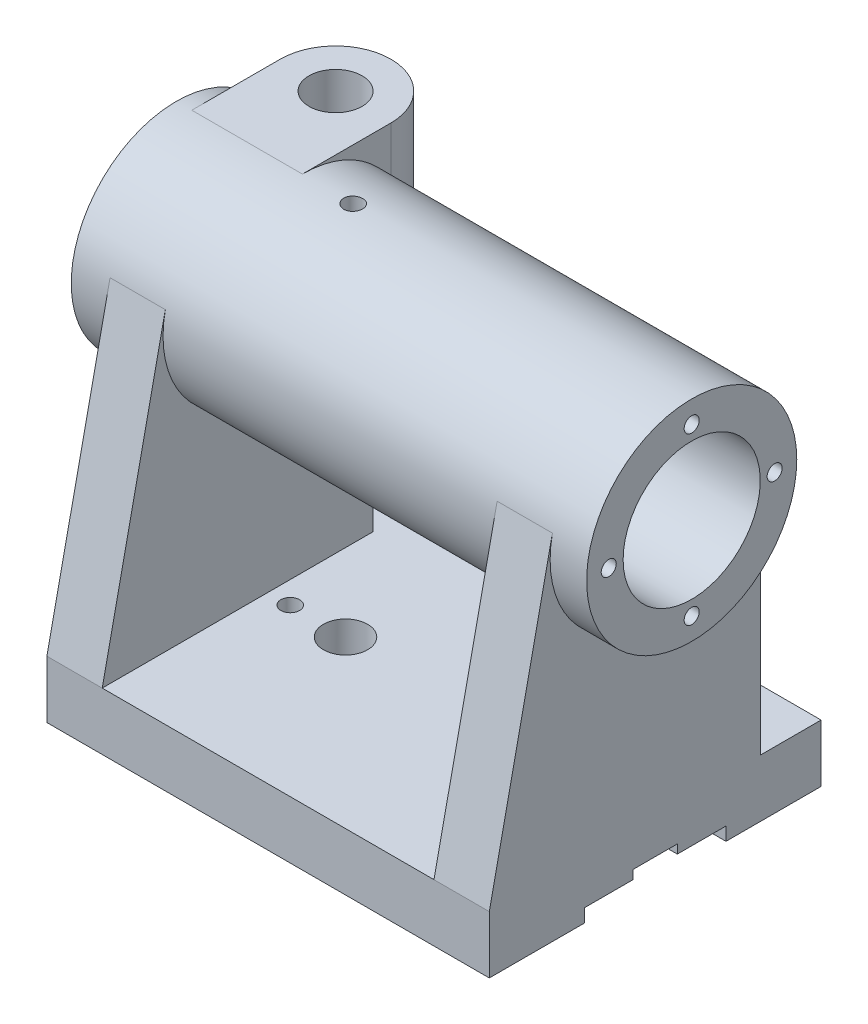
SolidWorks part; units mm, degrees
ref_plane "前视基准面" through (0, 0, 0) normal (0, 0, 1) x (1, 0, 0)
ref_plane "上视基准面" through (0, 0, 0) normal (0, 1, 0) x (1, 0, 0)
ref_plane "右视基准面" through (0, 0, 0) normal (1, 0, 0) x (0, 0, -1)
sketch "草图2" plane through (0, 0, 0) normal (1, 0, 0) x (0, 0, -1)
  circle A0 centre (0, 0) radius 47.5
  dimension "D1" = 95
extrude "凸台-拉伸1" add sketch "草图2" along normal blind 233
sketch "草图4" plane through (0, 0, 0) normal (0, 1, 0) x (1, 0, 0)
  line L0 (32, 0) -> (32, 40) construction
  line L1 (7, 0) -> (7, 40)
  line L2 (57, 0) -> (57, 40)
  line L3 (7, 0) -> (57, 0)
  line L4 (0, 47.5) -> (0, -47.5) construction
  arc A0 (7, 0) -> (57, 0) centre (32, 0) ccw
  arc A1 (57, 40) -> (7, 40) centre (32, 40) ccw
  point P2 (32, 20)
  dimension "D1" = 25
  dimension "D2" = 40
  dimension "D3" = 32
extrude "凸台-拉伸2" add sketch "草图4" along normal mid plane 95
ref_plane "基准面4" through (0, -150, 0) normal (0, 1, 0) x (1, 0, 0)
sketch "草图6" plane through (0, -150, 0) normal (0, 1, 0) x (1, 0, 0)
  line L0 (0, -47.5) -> (233, -47.5) construction
  line L1 (216.5, -75) -> (16.5, -75)
  line L2 (216.5, -75) -> (216.5, 75)
  line L3 (216.5, 75) -> (16.5, 75)
  line L4 (16.5, -75) -> (16.5, 75)
  line L5 (216.5, -75) -> (16.5, 75) construction
  line L6 (216.5, 75) -> (16.5, -75) construction
  line L7 (0, -47.5) -> (233, -47.5) construction
  point P0 (116.5, 0)
  point P8 (116.5, -47.5)
  dimension "D1" = 150
  dimension "D2" = 200
extrude "凸台-拉伸3" add sketch "草图6" along normal blind 26 separate body
sketch "草图7" plane through (16.5, 0, 0) normal (-1, 0, 0) x (0, 0, 1)
  line L0 (-75, -150) -> (75, -150) construction
  line L1 (-32, -156) -> (32, -156)
  line L2 (-32, -156) -> (-32, -144)
  line L3 (-32, -144) -> (32, -144)
  line L4 (32, -156) -> (32, -144)
  line L5 (-32, -156) -> (32, -144) construction
  line L6 (-32, -144) -> (32, -156) construction
  point P0 (0, -150)
  dimension "D1" = 12
  dimension "D2" = 64
extrude "切除-拉伸2" cut sketch "草图7" against normal through all both and the other way through all
sketch "草图9" plane through (0, -124, 0) normal (0, 1, 0) x (1, 0, 0)
  line L0 (116.5, -75) -> (116.5, 75) construction
  line L1 (16.5, -75) -> (216.5, -75) construction
  line L2 (216.5, 75) -> (16.5, 75) construction
  circle A0 centre (76.5, 0) radius 10
  circle A1 centre (156.5, 0) radius 10
  dimension "D1" = 20
  dimension "D2" = 80
extrude "切除-拉伸3" cut sketch "草图9" against normal up to next (20 mm away)
sketch "草图10" plane through (0, -124, 0) normal (0, 1, 0) x (1, 0, 0)
  line L0 (116.5, -75) -> (116.5, 75) construction
  line L1 (116.5, -75) -> (116.5, 75) construction
  line L2 (216.5, -75) -> (216.5, 75) construction
  point P0 (181.5, 0)
  point P6 (51.5, 0)
  dimension "D1" = 35
hole_wizard "M10 螺纹孔的螺纹孔钻头1" positions "草图10" profile "草图11" hole size "M10" standard "GB" end condition up to next
sketch "草图11" plane through (181.5, -124, 0) normal (1, 0, 0) x (0, 0, 1)
  line L0 (0, 0) -> (0, 20.001)
  line L1 (0, 20.001) -> (4.25, 20.001)
  line L2 (4.25, 20.001) -> (4.25, 0)
  line L5 (4.25, 0) -> (0, 0)
  line L11 (0, -6.35) -> (0, 107.95) construction
  dimension "通孔孔直径" = 8.5
  dimension "通孔孔深度" = 20.001
sketch "草图12" plane through (16.5, 0, 0) normal (-1, 0, 0) x (0, 0, 1)
  line L0 (-32, -144) -> (32, -144) construction
  line L1 (-10, -148) -> (10, -148)
  line L2 (-10, -148) -> (-10, -140)
  line L3 (-10, -140) -> (10, -140)
  line L4 (10, -148) -> (10, -140)
  line L5 (-10, -148) -> (10, -140) construction
  line L6 (-10, -140) -> (10, -148) construction
  point P0 (0, -144)
  dimension "D1" = 8
  dimension "D2" = 20
extrude "切除-拉伸4" cut sketch "草图12" against normal up to next
ref_plane "基准面5" through (116.5, 0, 0) normal (-1, 0, 0) x (0, 0, 1)
mirror "镜向1" about plane through (116.5, 0, 0) normal (-1, 0, 0) of "切除-拉伸4"
sketch "草图13" plane through (16.5, 0, 0) normal (-1, 0, 0) x (0, 0, 1)
  line L0 (-75, -124) -> (75, -124) construction
  line L1 (-47.5, -124) -> (-35, -124)
  line L2 (-47.5, -124) -> (-47.5, -47.5)
  line L4 (-35, -124) -> (-35, -82.5)
  line L5 (0, -47.5) -> (-40, -47.5) construction
  line L9 (-47.5, -47.5) -> (0, -47.5)
  arc A0 (0, -47.5) -> (-35, -82.5) centre (0, -82.5) ccw
  arc A1 (-35, -82.5) -> (0, -47.5) centre (0, -82.5) ccw construction
  circle A2 centre (0, 0) radius 47.5 construction
  dimension "D2" = 70
sketch "草图15" plane through (0, 47.5, 0) normal (0, 1, 0) x (1, 0, 0)
  arc A0 (57, 40) -> (7, 40) centre (32, 40) ccw construction
  arc A1 (57, 40) -> (7, 40) centre (32, 40) ccw construction
  point P4 (32, 40)
sketch "草图16" plane through (0, 47.5, 0) normal (0, 1, 0) x (1, 0, 0)
  circle A0 centre (32, 40) radius 12
  dimension "D1" = 24
ref_plane "基准面6" through (32, 0, 0) normal (-1, 0, 0) x (0, 0, 1)
extrude "凸台-拉伸6" add sketch "草图13" against normal blind 25
sketch "草图18" plane through (16.5, 0, 0) normal (-1, 0, 0) x (0, 0, 1)
  line L0 (75, -124) -> (46.4562, 9.903)
  circle A0 centre (0, 0) radius 47.5 construction
rib "筋8" sketch "草图18" sketch "草图18" thickness 25 extrusion direction parallel to sketch draft on no parameters "D1"=25
sketch "草图19" plane through (216.5, 0, 0) normal (1, 0, 0) x (0, 0, -1)
  line L4 (47.5, -47.5) -> (0, -47.5)
  line L5 (-46.4562, 9.903) -> (-75, -124)
  line L6 (-75, -124) -> (47.5, -124)
  line L7 (47.5, -124) -> (47.5, -47.5)
  line L8 (47.5, -47.5) -> (0, -47.5)
  line L9 (-46.4562, 9.903) -> (-75, -124)
  line L10 (-75, -124) -> (47.5, -124)
  line L11 (47.5, -124) -> (47.5, -47.5)
  arc A1 (-46.4562, 9.903) -> (0, -47.5) centre (0, 0) ccw
  arc A2 (-46.4562, 9.903) -> (0, -47.5) centre (0, 0) ccw
  dimension "D1" = 0
extrude "凸台-拉伸7" add sketch "草图19" against normal blind 25
sketch "草图20" plane through (0, -47.5, 0) normal (0, 1, 0) x (1, 0, 0)
  line L4 (216.5, 0) -> (216.5, 47.5)
  line L5 (216.5, 47.5) -> (191.5, 47.5)
  line L6 (191.5, 47.5) -> (191.5, 0)
  line L7 (191.5, 0) -> (216.5, 0)
  line L8 (216.5, 0) -> (216.5, 47.5)
  line L9 (216.5, 47.5) -> (191.5, 47.5)
  line L10 (191.5, 47.5) -> (191.5, 0)
  line L11 (191.5, 0) -> (216.5, 0)
  dimension "D1" = 0
extrude "凸台-拉伸10" add sketch "草图20" along normal blind 50
sketch "草图3" plane through (0, 0, 0) normal (-1, 0, 0) x (0, 0, 1)
  circle A0 centre (0, 0) radius 31
  dimension "D1" = 62
extrude "切除-拉伸1" cut sketch "草图3" against normal through all both and the other way through all
sketch "草图22" plane through (0, 0, 0) normal (-1, 0, 0) x (0, 0, 1)
  circle A0 centre (0, 0) radius 37.5 construction
  point P3 (0, 37.5)
  point P4 (37.5, 0)
  point P5 (0, -37.5)
  point P6 (-37.5, 0)
  dimension "D1" = 75
hole_wizard "M8 螺纹孔1" positions "草图22" profile "草图25" tap size "M8" standard "GB"
sketch "草图25" plane through (0, 0, -37.5) normal (0, 1, 0) x (0, 0, 1)
  line L0 (0, 0) -> (0, 23)
  line L1 (0, 23) -> (3.4, 20.9571)
  line L2 (3.4, 20.9571) -> (3.4, 0)
  line L5 (3.4, 0) -> (0, 0)
  line L10 (0, 23) -> (-3.4, 20.9571) construction
  line L11 (0, -6.35) -> (0, 107.95) construction
  dimension "螺纹孔钻头直径" = 6.8
  dimension "螺纹孔钻头深度" = 23
  dimension "导头角度" = 118
cosmetic thread "孔螺纹线1" parameters "D1"=20, "D2"=8
cosmetic thread "孔螺纹线2" parameters "D1"=20, "D2"=8
cosmetic thread "孔螺纹线3" parameters "D1"=20, "D2"=8
cosmetic thread "孔螺纹线4" parameters "D1"=20, "D2"=8
mirror "镜向6" about plane through (116.5, 0, 0) normal (-1, 0, 0) of "M8 螺纹孔1"
sketch "草图26" plane through (0, 0, 0) normal (0, 1, 0) x (1, 0, 0)
  point P0 (80, 0)
  dimension "D1" = 80
hole_wizard "M10 螺纹孔1" positions "草图26" profile "草图27" tap size "M10" standard "GB"
sketch "草图27" plane through (80, 0, 0) normal (1, 0, 0) x (0, 0, -1)
  line L0 (0, 0) -> (0, 47.5)
  line L1 (0, 47.5) -> (4.25, 47.5)
  line L2 (4.25, 47.5) -> (4.25, 0)
  line L5 (4.25, 0) -> (0, 0)
  line L11 (0, -6.35) -> (0, 107.95) construction
  dimension "通孔螺纹孔钻头直径" = 8.5
  dimension "通孔螺纹孔钻头深度" = 47.5
cosmetic thread "孔螺纹线5" parameters "D2"=10
extrude "切除-拉伸6" cut sketch "草图16" against normal blind 85
